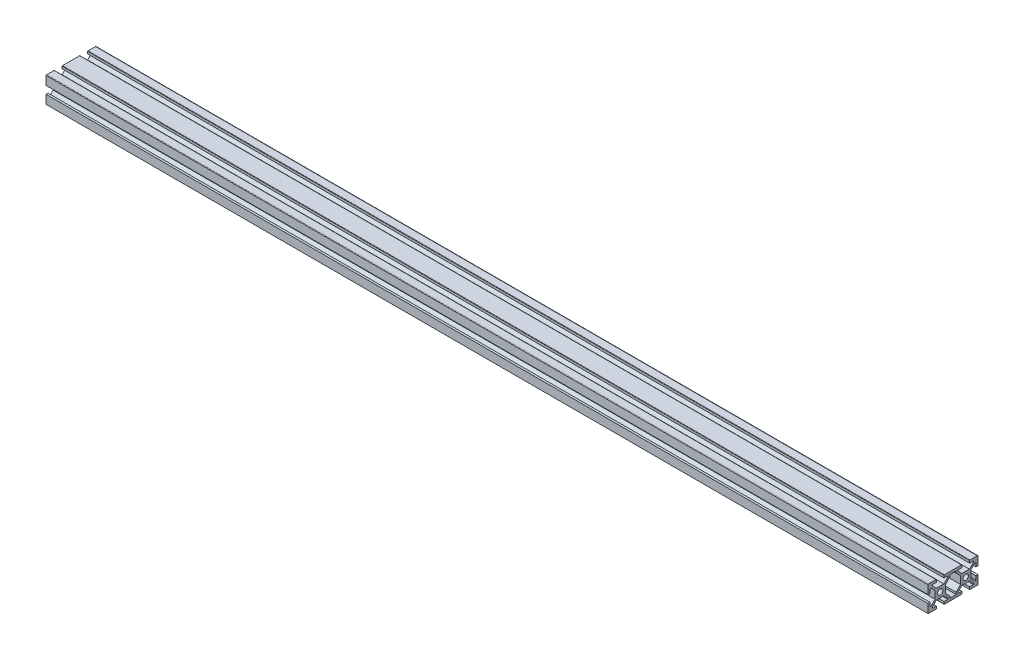
SolidWorks part; units mm, degrees
ref_plane "Front Plane" through (0, 0, 0) normal (0, 0, 1) x (1, 0, 0)
ref_plane "Top Plane" through (0, 0, 0) normal (0, 1, 0) x (1, 0, 0)
ref_plane "Right Plane" through (0, 0, 0) normal (1, 0, 0) x (0, 0, -1)
sketch "Sketch1" plane through (0, 0, 0) normal (0, 0, 1) x (1, 0, 0)
  line L0 (0, 0) -> (690, 0)
  dimension "D1" = 690
other "20xs5 20X40S5(1)"
ref_plane "Plane1" through (0, 0, 0) normal (1, 0, 0) x (0, 1, 0)
sketch "草图1" plane through (0, 0, 0) normal (1, 0, 0) x (0, 1, 0)
  line L0 (-10, 19) -> (-10, 13.3)
  line L1 (-9.7, 13) -> (-8, 13)
  line L2 (-8, 13) -> (-8, 16)
  line L3 (-8, 16) -> (-7.0607, 16)
  line L4 (-7.0607, 16) -> (-4, 12.9393)
  line L5 (-4, 12.9393) -> (-4, 7.0607)
  line L6 (-4, 7.0607) -> (-7.0607, 4)
  line L7 (-7.0607, 4) -> (-8, 4)
  line L8 (-8, 4) -> (-8, 7)
  line L9 (-8, 7) -> (-9.7, 7)
  line L10 (-10, 6.7) -> (-10, -6.7)
  line L11 (-9.7, -7) -> (-8, -7)
  line L12 (-8, -7) -> (-8, -4)
  line L13 (-8, -4) -> (-7.0607, -4)
  line L14 (-7.0607, -4) -> (-4, -7.0607)
  line L15 (-4, -7.0607) -> (-4, -12.9393)
  line L16 (-4, -12.9393) -> (-7.0607, -16)
  line L17 (-7.0607, -16) -> (-8, -16)
  line L18 (-8, -16) -> (-8, -13)
  line L19 (-8, -13) -> (-9.7, -13)
  line L20 (-10, -13.3) -> (-10, -19)
  line L21 (-9.8, -19.6) -> (-3, -19.6)
  line L22 (-3, -19.6) -> (-3, -18)
  line L23 (-3, -18) -> (-6, -18)
  line L24 (-6, -18) -> (-6, -17.0607)
  line L25 (-6, -17.0607) -> (-2.9393, -14)
  line L26 (-2.9393, -14) -> (2.9393, -14)
  line L27 (2.9393, -14) -> (6, -17.0607)
  line L28 (6, -17.0607) -> (6, -18)
  line L29 (6, -18) -> (3, -18)
  line L30 (3, -18) -> (3, -19.6)
  line L31 (3, -19.6) -> (9.8, -19.6)
  line L32 (10, -19) -> (10, -13.3)
  line L33 (9.7, -13) -> (8, -13)
  line L34 (8, -13) -> (8, -16)
  line L35 (8, -16) -> (7.0607, -16)
  line L36 (7.0607, -16) -> (4, -12.9393)
  line L37 (4, -12.9393) -> (4, -7.0607)
  line L38 (4, -7.0607) -> (7.0607, -4)
  line L39 (7.0607, -4) -> (8, -4)
  line L40 (8, -4) -> (8, -7)
  line L41 (8, -7) -> (9.7, -7)
  line L42 (10, -6.7) -> (10, 6.7)
  line L43 (9.7, 7) -> (8, 7)
  line L44 (8, 7) -> (8, 4)
  line L45 (8, 4) -> (7.0607, 4)
  line L46 (7.0607, 4) -> (4, 7.0607)
  line L47 (4, 7.0607) -> (4, 12.9393)
  line L48 (4, 12.9393) -> (7.0607, 16)
  line L49 (7.0607, 16) -> (8, 16)
  line L50 (8, 16) -> (8, 13)
  line L51 (8, 13) -> (9.7, 13)
  line L52 (10, 13.3) -> (10, 19)
  line L53 (9.8, 19.6) -> (3, 19.6)
  line L54 (3, 19.6) -> (3, 18)
  line L55 (3, 18) -> (6, 18)
  line L56 (6, 18) -> (6, 17.0607)
  line L57 (6, 17.0607) -> (2.9393, 14)
  line L58 (2.9393, 14) -> (-2.9393, 14)
  line L59 (-2.9393, 14) -> (-6, 17.0607)
  line L60 (-6, 17.0607) -> (-6, 18)
  line L61 (-6, 18) -> (-3, 18)
  line L62 (-3, 18) -> (-3, 19.6)
  line L63 (-3, 19.6) -> (-9.8, 19.6)
  line L64 (-8, -2.5) -> (-6.4393, -2.5)
  line L65 (-6.4393, -2.5) -> (-2.9393, -6)
  line L66 (-2.9393, -6) -> (2.9393, -6)
  line L67 (2.9393, -6) -> (6.4393, -2.5)
  line L68 (6.4393, -2.5) -> (8, -2.5)
  line L69 (8, -2.5) -> (8, 2.5)
  line L70 (8, 2.5) -> (6.4393, 2.5)
  line L71 (6.4393, 2.5) -> (2.9393, 6)
  line L72 (2.9393, 6) -> (-2.9393, 6)
  line L73 (-2.9393, 6) -> (-6.4393, 2.5)
  line L74 (-6.4393, 2.5) -> (-8, 2.5)
  line L75 (-8, 2.5) -> (-8, -2.5)
  arc A0 (-10, 13.3) -> (-9.7, 13) centre (-9.7, 13.3) ccw
  arc A1 (-9.7, 7) -> (-10, 6.7) centre (-9.7, 6.7) ccw
  arc A2 (-10, -6.7) -> (-9.7, -7) centre (-9.7, -6.7) ccw
  arc A3 (-9.7, -13) -> (-10, -13.3) centre (-9.7, -13.3) ccw
  arc A4 (-10, -19) -> (-9.8, -19.6) centre (-9, -19) ccw
  arc A5 (9.8, -19.6) -> (10, -19) centre (9, -19) ccw
  arc A6 (10, -13.3) -> (9.7, -13) centre (9.7, -13.3) ccw
  arc A7 (9.7, -7) -> (10, -6.7) centre (9.7, -6.7) ccw
  arc A8 (10, 6.7) -> (9.7, 7) centre (9.7, 6.7) ccw
  arc A9 (9.7, 13) -> (10, 13.3) centre (9.7, 13.3) ccw
  arc A10 (10, 19) -> (9.8, 19.6) centre (9, 19) ccw
  arc A11 (-9.8, 19.6) -> (-10, 19) centre (-9, 19) ccw
  circle A12 centre (0, -10) radius 2.1
  circle A13 centre (0, 10) radius 2.1
  point P104 (-10, 19.6)
  point P105 (0, 19.6)
  point P106 (10, 19.6)
  point P107 (10, 10)
  point P108 (10, -10)
  point P109 (10, -19.6)
  point P110 (0, -19.6)
  point P111 (-10, -19.6)
  point P112 (-10, -10)
  point P113 (-10, 10)
  point P114 (-10, 0)
  point P115 (10, 0)
  point P116 (0, 0)
